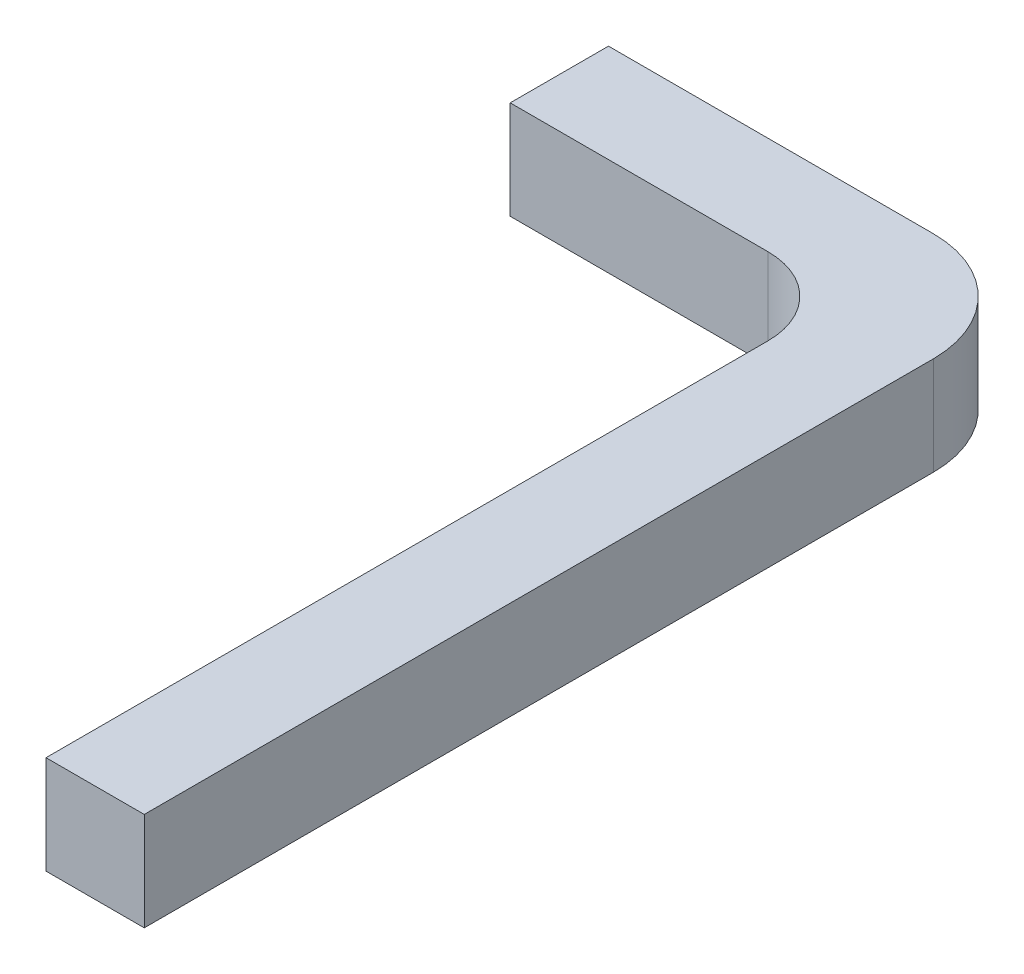
SolidWorks part; units mm, degrees
ref_plane "Front Plane" through (0, 0, 0) normal (0, 0, 1) x (1, 0, 0)
ref_plane "Top Plane" through (0, 0, 0) normal (0, 1, 0) x (1, 0, 0)
ref_plane "Right Plane" through (0, 0, 0) normal (1, 0, 0) x (0, 0, -1)
sketch "Sketch9" plane through (0, 0, 0) normal (0, 1, 0) x (1, 0, 0)
  line L1 (0, 0) -> (28, 0)
  line L2 (0, 0) -> (0, -6.35)
  line L3 (0, -6.35) -> (28, -6.35)
  line L4 (28, 0) -> (28, -6.35)
  line L5 (28, 0) -> (21.65, 0)
  line L6 (28, 0) -> (28, -58)
  line L7 (28, -58) -> (21.65, -58)
  line L8 (21.65, 0) -> (21.65, -58)
  dimension "D1" = 28
  dimension "D2" = 6.35
  dimension "D3" = 58
  dimension "D4" = 6.35
extrude "Boss-Extrude1" add sketch "Sketch9" along normal blind 6.35 contours L8 L1 L2 L3 | L1 L8 L3 L4 | L3 L8 L7 L6
fillet "Fillet2" radius 5 1 edges at (21.65, 3.175, 6.35)
fillet "Fillet3" radius 7 1 edges at (28, 3.175, 0)
